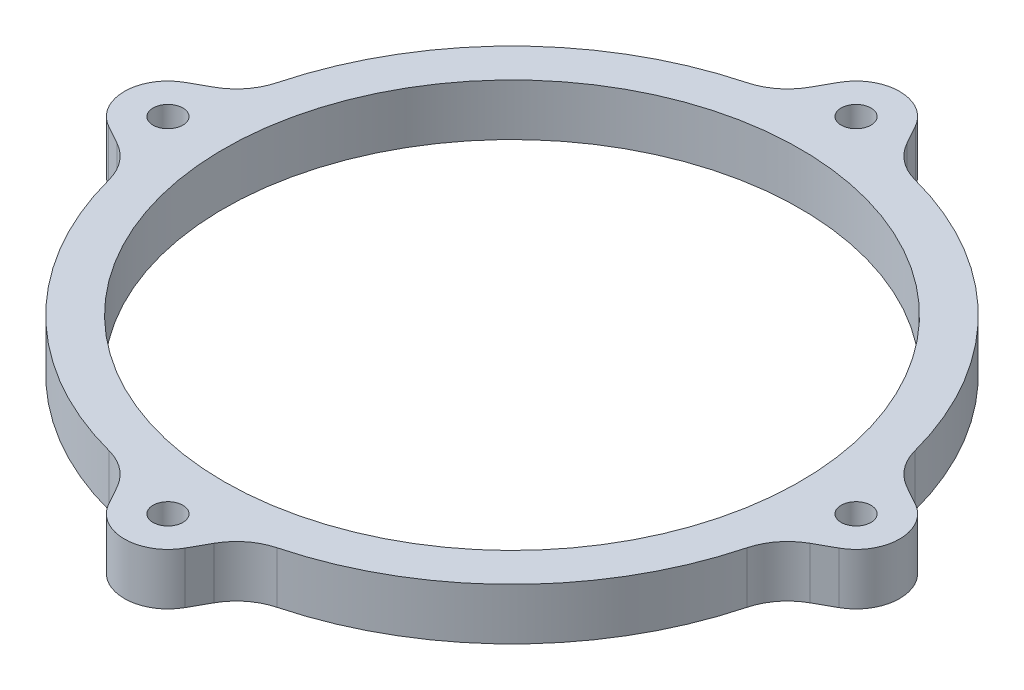
SolidWorks part; units mm, degrees
ref_plane "正面" through (0, 0, 0) normal (0, 0, 1) x (1, 0, 0)
ref_plane "平面" through (0, 0, 0) normal (0, 1, 0) x (1, 0, 0)
ref_plane "右側面" through (0, 0, 0) normal (1, 0, 0) x (0, 0, -1)
sketch "ｽｹｯﾁ1" plane through (0, 0, 0) normal (0, 1, 0) x (1, 0, 0)
  line L0 (0, 0) -> (0, 60) construction
  line L1 (-6.6411, 63.6954) -> (-10.6411, 56.5068)
  line L2 (6.6411, 63.6954) -> (10.6411, 56.5068)
  line L3 (63.6954, 6.6411) -> (56.5068, 10.6411)
  line L4 (63.6954, -6.6411) -> (56.5068, -10.6411)
  line L5 (6.6411, -63.6954) -> (10.6411, -56.5068)
  line L6 (-6.6411, -63.6954) -> (-10.6411, -56.5068)
  line L7 (-63.6954, -6.6411) -> (-56.5068, -10.6411)
  line L8 (-63.6954, 6.6411) -> (-56.5068, 10.6411)
  line L9 (-60, 0) -> (0, 0) construction
  line L10 (0, 0) -> (0, -60) construction
  arc A0 (-10.6411, 56.5068) -> (-56.5068, 10.6411) centre (0, 0) ccw
  circle A1 centre (0, 0) radius 50.25
  circle A2 centre (0, 60) radius 2.6
  arc A3 (6.6411, 63.6954) -> (-6.6411, 63.6954) centre (0, 60) ccw
  circle A4 centre (0, 60) radius 7.6 construction
  circle A5 centre (60, 0) radius 2.6
  arc A6 (63.6954, -6.6411) -> (63.6954, 6.6411) centre (60, 0) ccw
  circle A7 centre (0, -60) radius 2.6
  arc A8 (-6.6411, -63.6954) -> (6.6411, -63.6954) centre (0, -60) ccw
  circle A9 centre (-60, 0) radius 2.6
  arc A10 (-63.6954, 6.6411) -> (-63.6954, -6.6411) centre (-60, 0) ccw
  arc A11 (-56.5068, -10.6411) -> (-10.6411, -56.5068) centre (0, 0) ccw
  arc A12 (10.6411, -56.5068) -> (56.5068, -10.6411) centre (0, 0) ccw
  arc A13 (56.5068, 10.6411) -> (10.6411, 56.5068) centre (0, 0) ccw
  dimension "D1" = 100.5
  dimension "D2" = 115
  dimension "D3" = 60
  dimension "D4" = 5.2
  dimension "D6" = 4
  dimension "D5" = 5
  dimension "D7" = 4
extrude "ﾎﾞｽ - 押し出し1" add sketch "ｽｹｯﾁ1" along normal blind 9
fillet "ﾌｨﾚｯﾄ1" radius 10 8 edges at (56.5068, 4.5, 10.6411) (56.5068, 4.5, -10.6411) (10.6411, 4.5, -56.5068) (-10.6411, 4.5, -56.5068) (-56.5068, 4.5, -10.6411) (-56.5068, 4.5, 10.6411) (-10.6411, 4.5, 56.5068) (10.6411, 4.5, 56.5068)
